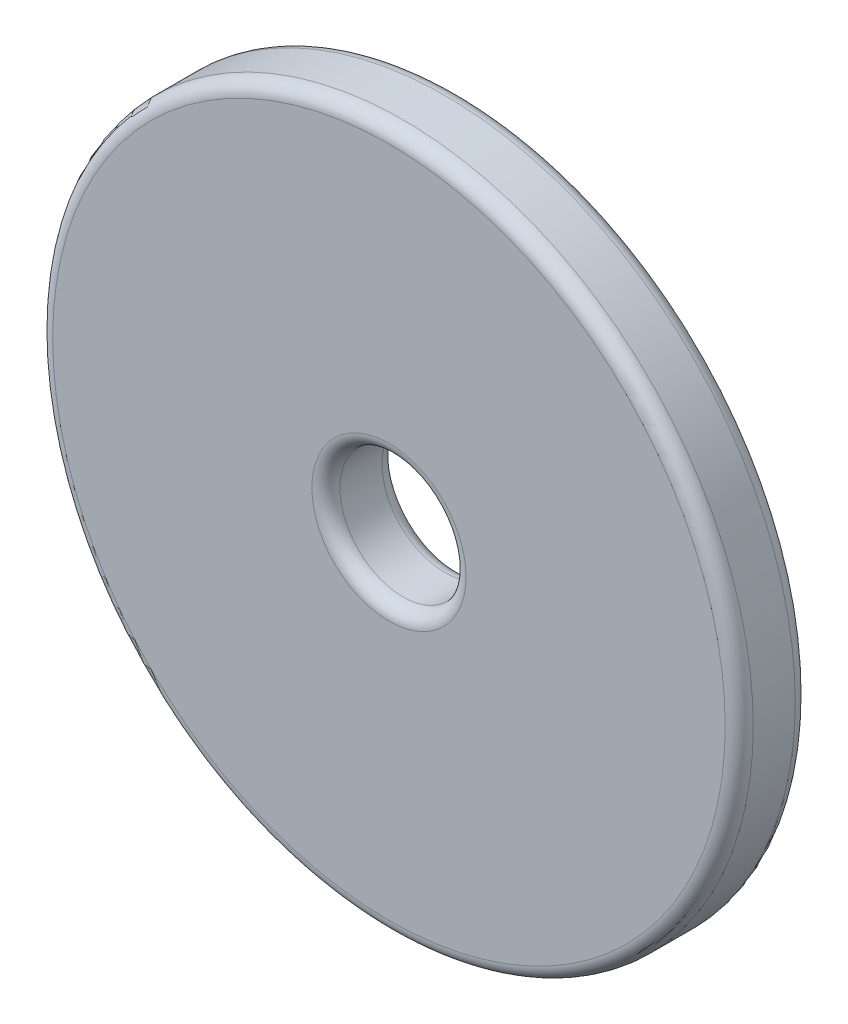
SolidWorks part; units mm, degrees
ref_plane "Front Plane" through (0, 0, 0) normal (0, 0, 1) x (1, 0, 0)
ref_plane "Top Plane" through (0, 0, 0) normal (0, 1, 0) x (1, 0, 0)
ref_plane "Right Plane" through (0, 0, 0) normal (1, 0, 0) x (0, 0, -1)
sketch "Sketch1" plane through (0, 0, 0) normal (0, 0, 1) x (1, 0, 0)
  line L0 (0, 0) -> (0, 33.5) construction
  line L1 (0, 33.5) -> (0, 45) construction
  circle A0 centre (0, 0) radius 45
  circle A1 centre (0, 0) radius 2.25
  circle A2 centre (0, 33.5) radius 1.75
  circle A3 centre (33.5, 0) radius 1.75
  circle A4 centre (0, -33.5) radius 1.75
  circle A5 centre (-33.5, 0) radius 1.75
  point P16 (0, 0)
  dimension "D1" = 3.5
  dimension "D2" = 4.5
  dimension "D3" = 90
  dimension "D4" = 33.5
  dimension "D5" = 4
extrude "Boss-Extrude1" add sketch "Sketch1" along normal blind 2.5
sketch "Sketch2" plane through (0, 0, 0) normal (0, 0, -1) x (-1, 0, 0)
  circle A0 centre (0, 0) radius 29.85
  circle A1 centre (0, 0) radius 12.65
  dimension "D1" = 59.7
  dimension "D2" = 25.3
extrude "Boss-Extrude2" add sketch "Sketch2" along normal blind 1
sketch "Sketch3" plane through (0, 0, 0) normal (0, 0, 1) x (1, 0, 0)
  circle A0 centre (0, 0) radius 45
  circle A1 centre (0, 0) radius 12.5
  circle A2 centre (0, 0) radius 45 construction
  dimension "D1" = 25
extrude "Cut-Extrude1" cut sketch "Sketch3" against normal through all both and the other way through all
fillet "Fillet1" radius 0.5 4 edges at (12.5, 0, 2.5) (2.25, 0, 2.5) (2.25, 0, 0) (12.5, 0, 0)
